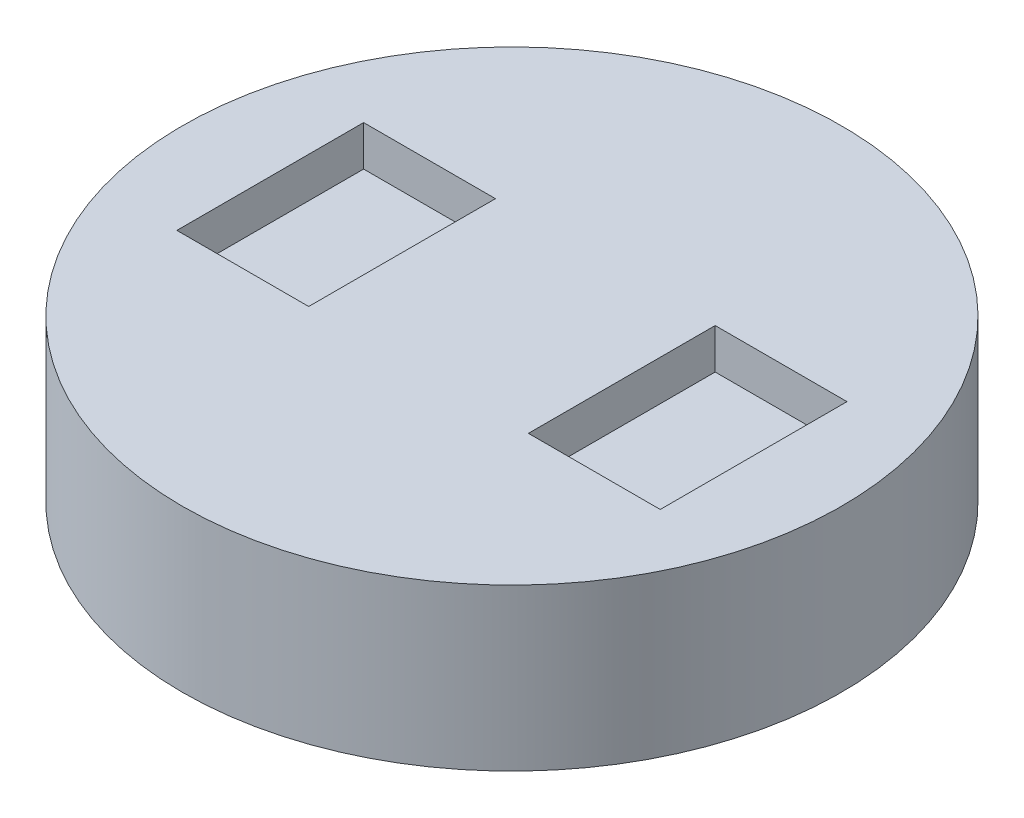
SolidWorks part; units mm, degrees
ref_plane "Front Plane" through (0, 0, 0) normal (0, 0, 1) x (1, 0, 0)
ref_plane "Top Plane" through (0, 0, 0) normal (0, 1, 0) x (1, 0, 0)
ref_plane "Right Plane" through (0, 0, 0) normal (1, 0, 0) x (0, 0, -1)
sketch "Sketch1" plane through (0, 0, 0) normal (0, 1, 0) x (1, 0, 0)
  circle A0 centre (0, 0) radius 18
  dimension "D1" = 36
extrude "Boss-Extrude1" add sketch "Sketch1" along normal blind 8.8
sketch "Sketch2" plane through (0, 8.8, 0) normal (0, 1, 0) x (1, 0, 0)
  line L0 (0, 0) -> (21.4151, 0) construction
  line L1 (-13.2, 5.1) -> (-6, 5.1)
  line L2 (-13.2, 5.1) -> (-13.2, -5.1)
  line L3 (-13.2, -5.1) -> (-6, -5.1)
  line L4 (-6, 5.1) -> (-6, -5.1)
  line L5 (0, 0) -> (0, 18.5778) construction
  line L10 (13.2, -5.1) -> (6, -5.1)
  line L11 (6, 5.1) -> (6, -5.1)
  line L12 (13.2, 5.1) -> (6, 5.1)
  line L13 (13.2, 5.1) -> (13.2, -5.1)
  dimension "D3" = 5.1
  dimension "D1" = 10.2
  dimension "D2" = 7.2
  dimension "D4" = 6
extrude "Cut-Extrude1" cut sketch "Sketch2" against normal blind 2.2
